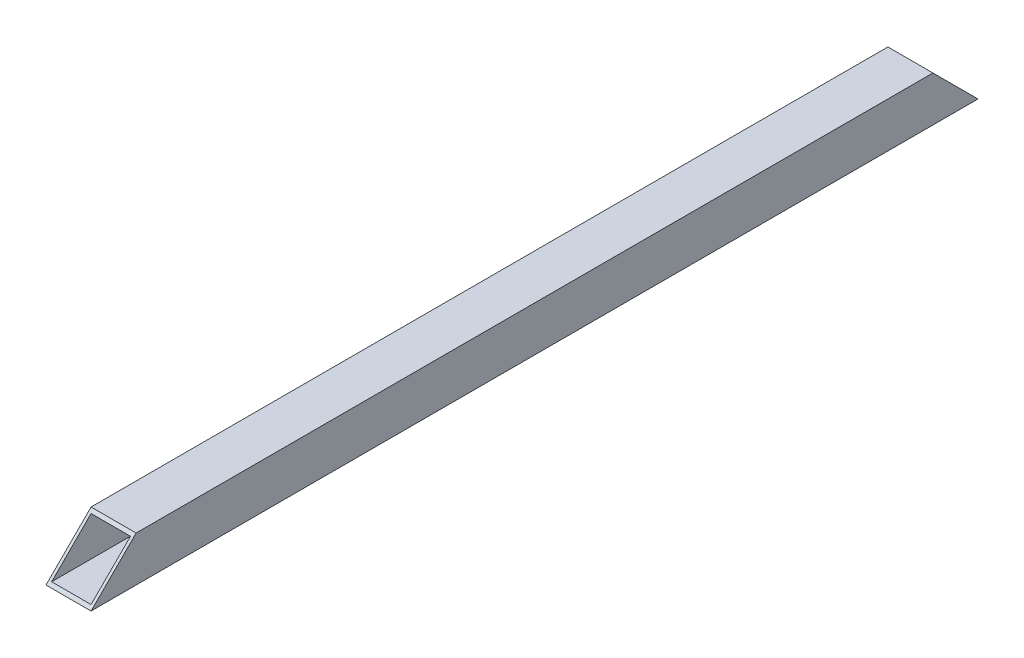
SolidWorks part; units mm, degrees
material "6061-T6 (SS)"
ref_plane "Front Plane" through (0, 0, 0) normal (0, 0, 1) x (1, 0, 0)
ref_plane "Top Plane" through (0, 0, 0) normal (0, 1, 0) x (1, 0, 0)
ref_plane "Right Plane" through (0, 0, 0) normal (1, 0, 0) x (0, 0, -1)
sketch "Sketch1" plane through (0, 0, 0) normal (0, 0, 1) x (1, 0, 0)
  line L1 (12.7, -12.7) -> (-12.7, -12.7)
  line L2 (12.7, -12.7) -> (12.7, 12.7)
  line L3 (12.7, 12.7) -> (-12.7, 12.7)
  line L4 (-12.7, -12.7) -> (-12.7, 12.7)
  line L5 (12.7, -12.7) -> (-12.7, 12.7) construction
  line L6 (12.7, 12.7) -> (-12.7, -12.7) construction
  line L7 (11.1125, -11.1125) -> (-11.1125, -11.1125)
  line L8 (11.1125, -11.1125) -> (11.1125, 11.1125)
  line L9 (11.1125, 11.1125) -> (-11.1125, 11.1125)
  line L10 (-11.1125, -11.1125) -> (-11.1125, 11.1125)
  line L11 (11.1125, -11.1125) -> (-11.1125, 11.1125) construction
  line L12 (11.1125, 11.1125) -> (-11.1125, -11.1125) construction
  point P0 (0, 0)
  point P6 (0, 0)
  point P11 (-12.7, 0)
  dimension "D1" = 25.4
  dimension "D2" = 25.4
  dimension "D3" = 1.5875
  dimension "D4" = 1.5875
extrude "Boss-Extrude1" add sketch "Sketch1" along normal mid plane 500
sketch "Sketch2" plane through (12.7, 0, 0) normal (1, 0, 0) x (0, 0, -1)
  line L0 (-250, -12.7) -> (-250, 12.7)
  line L1 (-250, 12.7) -> (-224.6, 12.7)
  line L2 (-250, 12.7) -> (250, 12.7) construction
  line L3 (-224.6, 12.7) -> (-250, -12.7)
  line L4 (250, -12.7) -> (250, 12.7)
  line L5 (250, 12.7) -> (224.6, 12.7)
  line L6 (224.6, 12.7) -> (250, -12.7)
  dimension "D1" = 45
  dimension "D2" = 45
extrude "Cut-Extrude1" cut sketch "Sketch2" against normal through all
